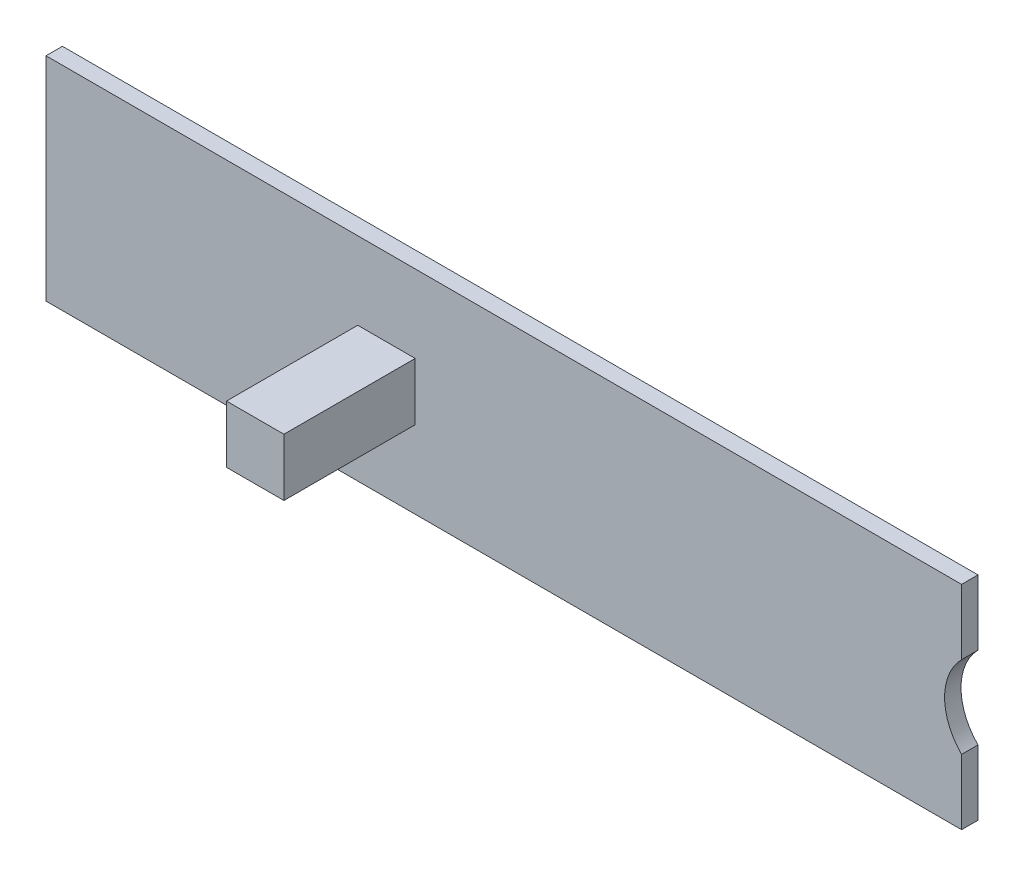
SolidWorks part; units mm, degrees
ref_plane "Plan de face" through (0, 0, 0) normal (0, 0, 1) x (1, 0, 0)
ref_plane "Plan de dessus" through (0, 0, 0) normal (0, 1, 0) x (1, 0, 0)
ref_plane "Plan de droite" through (0, 0, 0) normal (1, 0, 0) x (0, 0, -1)
sketch "Esquisse1" plane through (0, 0, 0) normal (0, 0, 1) x (1, 0, 0)
  line L1 (0, 0) -> (111.6, 0)
  line L2 (0, 0) -> (0, 25.9)
  line L3 (0, 25.9) -> (111.6, 25.9)
  line L4 (111.6, 0) -> (111.6, 25.9)
  dimension "D1" = 111.6
  dimension "D2" = 25.9
extrude "Boss.-Extru.1" add sketch "Esquisse1" along normal blind 2
sketch "Esquisse2" plane through (0, 0, 2) normal (0, 0, 1) x (1, 0, 0)
  line L0 (0, 25.9) -> (0, 0) construction
  line L1 (38, 16.45) -> (45, 16.45)
  line L2 (38, 16.45) -> (38, 9.45)
  line L3 (38, 9.45) -> (45, 9.45)
  line L4 (45, 16.45) -> (45, 9.45)
  line L5 (0, 12.95) -> (111.6, 12.95) construction
  line L6 (111.6, 0) -> (111.6, 25.9) construction
  point P10 (38, 12.95)
  dimension "D1" = 45
  dimension "D2" = 7
  dimension "D3" = 7
extrude "Boss.-Extru.2" add sketch "Esquisse2" along normal blind 16
sketch "Esquisse3" plane through (0, 0, 0) normal (0, 0, -1) x (-1, 0, 0)
  line L0 (-111.6, 0) -> (-111.6, 25.9) construction
  line L1 (0, 12.95) -> (-111.6, 12.95) construction
  line L2 (0, 25.9) -> (0, 0) construction
  line L3 (-111.6, 7.95) -> (-111.6, 17.95)
  arc A0 (-111.6, 7.95) -> (-111.6, 17.95) centre (-116.6, 12.95) ccw
  dimension "D1" = 10
  dimension "D2" = 5
extrude "Enlèv. mat.-Extru.1" cut sketch "Esquisse3" against normal up to surface (2 mm away) up to face at (55.8, 12.95, 2)
